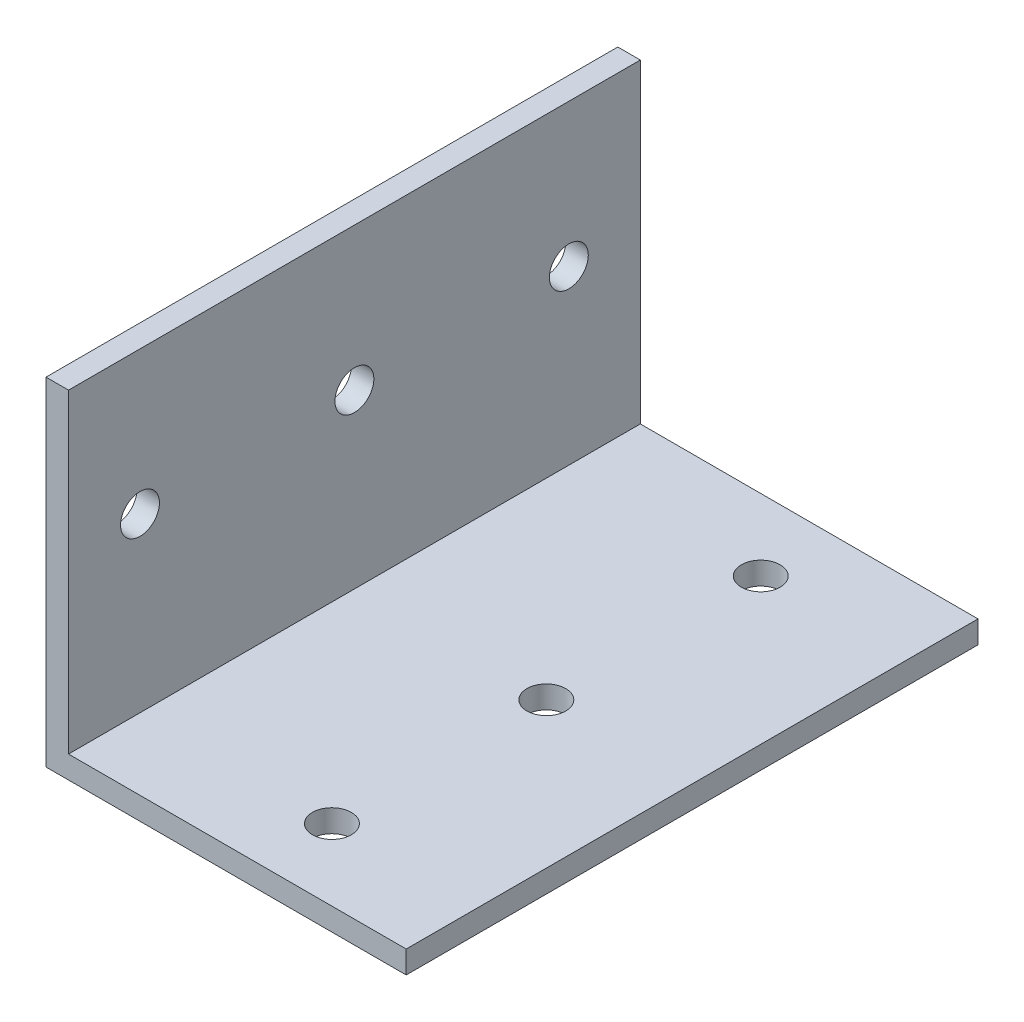
SolidWorks part; units mm, degrees
ref_plane "Front Plane" through (0, 0, 0) normal (0, 0, 1) x (1, 0, 0)
ref_plane "Top Plane" through (0, 0, 0) normal (0, 1, 0) x (1, 0, 0)
ref_plane "Right Plane" through (0, 0, 0) normal (1, 0, 0) x (0, 0, -1)
sketch "Sketch1" plane through (0, 0, 0) normal (0, 0, 1) x (1, 0, 0)
  line L0 (0, 0) -> (0, -30)
  line L1 (0, -30) -> (32, -30)
  line L2 (32, -30) -> (32, -28)
  line L3 (0, 0) -> (2, 0)
  line L4 (2, 0) -> (2, -28)
  line L5 (2, -28) -> (32, -28)
  dimension "D1" = 2
  dimension "D2" = 2
  dimension "D3" = 30
  dimension "D4" = 30
extrude "Boss-Extrude1" add sketch "Sketch1" along normal blind 50.8
hole_wizard "Tap Drill for #8-32 Tap1" positions "Sketch3" profile "Sketch2" hole size "#8-32" standard "ANSI Inch" end condition up to next
sketch "Sketch3" plane through (0, -28, 0) normal (0, 1, 0) x (1, 0, 0)
  line L13 (32, 0) -> (2, 0) construction
  point P0 (19.05, -6.35)
  point P2 (19.05, -44.45)
  point P43 (19.05, -25.4)
  dimension "D1" = 19.05
  dimension "D2" = 19.05
  dimension "D3" = 6.35
sketch "Sketch2" plane through (19.05, -28, 6.35) normal (1, 0, 0) x (0, 0, 1)
  line L0 (0, 0) -> (0, 2)
  line L1 (0, 2) -> (1.7272, 2)
  line L2 (1.7272, 2) -> (1.7272, 0)
  line L5 (1.7272, 0) -> (0, 0)
  line L11 (0, -6.35) -> (0, 107.95) construction
  dimension "Thru Hole Dia." = 3.4544
  dimension "Thru Hole Depth" = 2
hole_wizard "Tap Drill for #8-32 Tap2" positions "Sketch6" profile "Sketch5" hole size "#8-32" standard "ANSI Inch" end condition up to next
sketch "Sketch6" plane through (2, 0, 0) normal (1, 0, 0) x (0, 0, -1)
  line L5 (-50.8, -28) -> (-50.8, 0) construction
  line L6 (-50.8, 0) -> (0, 0) construction
  point P0 (-44.45, -12.7)
  point P2 (-6.35, -12.7)
  point P18 (-25.4, -12.7)
  dimension "D1" = 19.05
  dimension "D2" = 19.05
  dimension "D3" = 6.35
  dimension "D4" = 12.7
sketch "Sketch5" plane through (2, -12.7, 44.45) normal (0, 1, 0) x (0, 0, -1)
  line L0 (0, 0) -> (0, 2)
  line L1 (0, 2) -> (1.7272, 2)
  line L2 (1.7272, 2) -> (1.7272, 0)
  line L5 (1.7272, 0) -> (0, 0)
  line L11 (0, -6.35) -> (0, 107.95) construction
  dimension "Thru Hole Dia." = 3.4544
  dimension "Thru Hole Depth" = 2
equation "\".75ibn\"=6.35"
